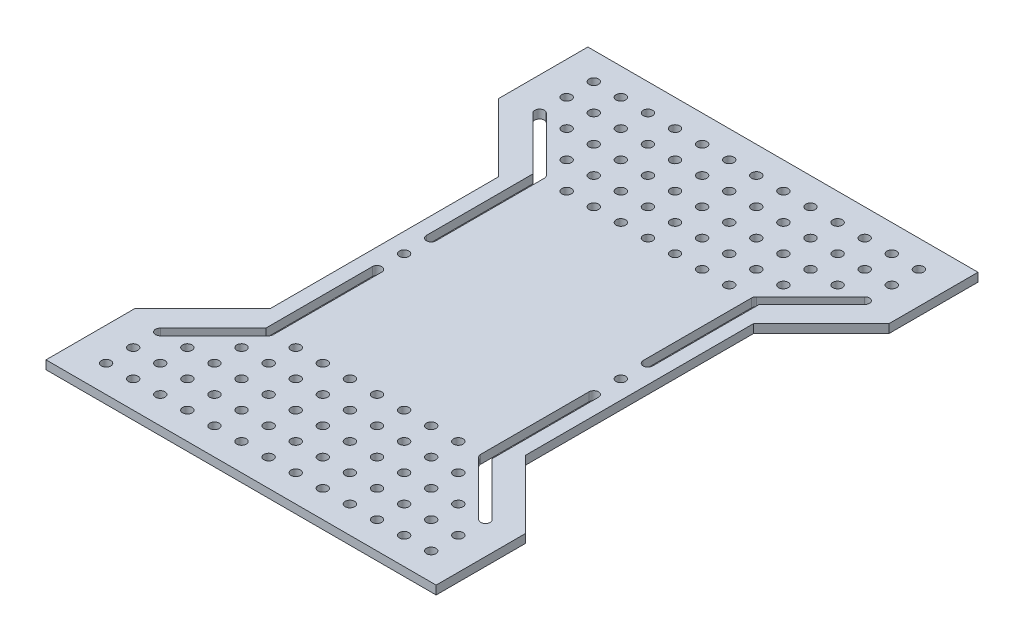
SolidWorks part; units mm, degrees
ref_plane "Alzado" through (0, 0, 0) normal (0, 0, 1) x (1, 0, 0)
ref_plane "Planta" through (0, 0, 0) normal (0, 1, 0) x (1, 0, 0)
ref_plane "Vista lateral" through (0, 0, 0) normal (1, 0, 0) x (0, 0, -1)
sketch "Croquis1" plane through (0, 0, 0) normal (0, 1, 0) x (1, 0, 0)
  point P0 (-19.4051, -35.8137)
  line B0 (25, 142.1) -> (25, 57.9)
  line B1 (25, 57.9) -> (0, 32.9)
  line B2 (0, 32.9) -> (0, 0)
  line B3 (0, 0) -> (144, 0)
  line B4 (144, 0) -> (144, 32.9)
  line B5 (144, 32.9) -> (119, 57.9)
  line B6 (119, 57.9) -> (119, 142.1)
  line B7 (119, 142.1) -> (144, 167.1)
  line B8 (144, 167.1) -> (144, 200)
  line B9 (144, 200) -> (0, 200)
  line B10 (0, 200) -> (0, 167.1)
  line B11 (0, 167.1) -> (25, 142.1)
  circle B12 centre (62.175, 20) radius 1.75
  circle B13 centre (92.175, 10) radius 1.75
  circle B14 centre (122.175, 10) radius 1.75
  circle B15 centre (132.175, 10) radius 1.75
  circle B16 centre (102.175, 10) radius 1.75
  circle B17 centre (112.175, 10) radius 1.75
  circle B18 centre (42.175, 20) radius 1.75
  circle B19 centre (52.175, 20) radius 1.75
  circle B20 centre (22.175, 20) radius 1.75
  circle B21 centre (32.175, 20) radius 1.75
  circle B22 centre (42.175, 10) radius 1.75
  circle B23 centre (52.175, 10) radius 1.75
  circle B24 centre (22.175, 10) radius 1.75
  circle B25 centre (32.175, 10) radius 1.75
  circle B26 centre (72.175, 10) radius 1.75
  circle B27 centre (122.175, 40) radius 1.75
  circle B28 centre (32.175, 50) radius 1.75
  circle B29 centre (102.175, 40) radius 1.75
  circle B30 centre (112.175, 40) radius 1.75
  circle B31 centre (72.175, 40) radius 1.75
  circle B32 centre (62.175, 40) radius 1.75
  circle B33 centre (92.175, 40) radius 1.75
  circle B34 centre (82.175, 40) radius 1.75
  circle B35 centre (122.175, 30) radius 1.75
  circle B36 centre (132.175, 30) radius 1.75
  circle B37 centre (102.175, 30) radius 1.75
  circle B38 centre (112.175, 30) radius 1.75
  circle B39 centre (42.175, 40) radius 1.75
  circle B40 centre (52.175, 40) radius 1.75
  circle B41 centre (22.175, 40) radius 1.75
  circle B42 centre (32.175, 40) radius 1.75
  circle B43 centre (132.175, 180) radius 1.75
  circle B44 centre (22.175, 190) radius 1.75
  circle B45 centre (12.175, 30) radius 1.75
  circle B46 centre (12.175, 170) radius 1.75
  circle B47 centre (12.175, 190) radius 1.75
  circle B48 centre (12.175, 180) radius 1.75
  circle B49 centre (12.175, 20) radius 1.75
  circle B50 centre (132.175, 190) radius 1.75
  circle B51 centre (92.175, 190) radius 1.75
  circle B52 centre (102.175, 190) radius 1.75
  circle B53 centre (112.175, 180) radius 1.75
  circle B54 centre (122.175, 180) radius 1.75
  circle B55 centre (92.175, 180) radius 1.75
  circle B56 centre (102.175, 180) radius 1.75
  circle B57 centre (32.175, 190) radius 1.75
  circle B58 centre (42.175, 190) radius 1.75
  circle B59 centre (42.175, 30) radius 1.75
  circle B60 centre (52.175, 30) radius 1.75
  circle B61 centre (22.175, 30) radius 1.75
  circle B62 centre (32.175, 30) radius 1.75
  circle B63 centre (82.175, 30) radius 1.75
  circle B64 centre (92.175, 30) radius 1.75
  circle B65 centre (62.175, 30) radius 1.75
  circle B66 centre (72.175, 30) radius 1.75
  circle B67 centre (92.175, 20) radius 1.75
  circle B68 centre (72.175, 20) radius 1.75
  circle B69 centre (122.175, 20) radius 1.75
  circle B70 centre (132.175, 20) radius 1.75
  circle B71 centre (102.175, 20) radius 1.75
  circle B72 centre (112.175, 20) radius 1.75
  circle B73 centre (32.175, 60) radius 1.75
  circle B74 centre (62.175, 50) radius 1.75
  circle B75 centre (72.175, 50) radius 1.75
  circle B76 centre (42.175, 50) radius 1.75
  circle B77 centre (52.175, 50) radius 1.75
  circle B78 centre (102.175, 50) radius 1.75
  circle B79 centre (112.175, 50) radius 1.75
  circle B80 centre (82.175, 50) radius 1.75
  circle B81 centre (92.175, 50) radius 1.75
  circle B82 centre (32.175, 70) radius 1.75
  circle B83 centre (112.175, 60) radius 1.75
  circle B84 centre (32.175, 80) radius 1.75
  circle B85 centre (112.175, 70) radius 1.75
  circle B86 centre (32.175, 90) radius 1.75
  circle B87 centre (112.175, 80) radius 1.75
  circle B88 centre (32.175, 100) radius 1.75
  circle B89 centre (112.175, 90) radius 1.75
  circle B90 centre (32.175, 110) radius 1.75
  circle B91 centre (112.175, 100) radius 1.75
  circle B92 centre (32.175, 120) radius 1.75
  circle B93 centre (112.175, 110) radius 1.75
  circle B94 centre (102.175, 160) radius 1.75
  circle B95 centre (112.175, 160) radius 1.75
  circle B96 centre (82.175, 160) radius 1.75
  circle B97 centre (92.175, 160) radius 1.75
  circle B98 centre (32.175, 170) radius 1.75
  circle B99 centre (42.175, 170) radius 1.75
  circle B100 centre (42.175, 150) radius 1.75
  circle B101 centre (52.175, 150) radius 1.75
  circle B102 centre (92.175, 150) radius 1.75
  circle B103 centre (82.175, 150) radius 1.75
  circle B104 centre (32.175, 150) radius 1.75
  circle B105 centre (112.175, 140) radius 1.75
  circle B106 centre (32.175, 130) radius 1.75
  circle B107 centre (112.175, 120) radius 1.75
  circle B108 centre (72.175, 190) radius 1.75
  circle B109 centre (82.175, 190) radius 1.75
  circle B110 centre (52.175, 190) radius 1.75
  circle B111 centre (62.175, 190) radius 1.75
  circle B112 centre (112.175, 190) radius 1.75
  circle B113 centre (122.175, 190) radius 1.75
  circle B114 centre (62.175, 150) radius 1.75
  circle B115 centre (72.175, 150) radius 1.75
  circle B116 centre (32.175, 140) radius 1.75
  circle B117 centre (42.175, 160) radius 1.75
  circle B118 centre (52.175, 160) radius 1.75
  circle B119 centre (32.175, 180) radius 1.75
  circle B120 centre (42.175, 180) radius 1.75
  circle B121 centre (82.175, 180) radius 1.75
  circle B122 centre (72.175, 180) radius 1.75
  circle B123 centre (22.175, 180) radius 1.75
  circle B124 centre (132.175, 170) radius 1.75
  circle B125 centre (32.175, 160) radius 1.75
  circle B126 centre (22.175, 160) radius 1.75
  circle B127 centre (22.175, 170) radius 1.75
  circle B128 centre (122.175, 160) radius 1.75
  circle B129 centre (102.175, 150) radius 1.75
  circle B130 centre (112.175, 150) radius 1.75
  circle B131 centre (62.175, 160) radius 1.75
  circle B132 centre (72.175, 160) radius 1.75
  circle B133 centre (92.175, 170) radius 1.75
  circle B134 centre (102.175, 170) radius 1.75
  circle B135 centre (112.175, 130) radius 1.75
  circle B136 centre (52.175, 180) radius 1.75
  circle B137 centre (62.175, 180) radius 1.75
  circle B138 centre (72.175, 170) radius 1.75
  circle B139 centre (82.175, 170) radius 1.75
  circle B140 centre (52.175, 170) radius 1.75
  circle B141 centre (62.175, 170) radius 1.75
  circle B142 centre (112.175, 170) radius 1.75
  circle B143 centre (122.175, 170) radius 1.75
  circle B144 centre (12.175, 10) radius 1.75
  circle B145 centre (62.175, 10) radius 1.75
  circle B146 centre (82.175, 20) radius 1.75
  circle B147 centre (82.175, 10) radius 1.75
sketch_block_instance "Bloque1-1"
sketch_block "Bloque1"
extrude "Saliente-Extruir1" add sketch "Croquis1" along normal blind 3.175
sketch "Croquis2" plane through (0, 3.175, 0) normal (0, 1, 0) x (1, 0, 0)
  line L0 (32.175, 150) -> (32.175, 110) construction
  line L3 (25, 100) -> (119, 100) construction
  line L4 (25, 142.1) -> (25, 57.9) construction
  line L5 (119, 57.9) -> (119, 142.1) construction
  line L9 (33.925, 150) -> (33.925, 110)
  line L10 (30.425, 150) -> (30.425, 110)
  line L11 (32.175, 50) -> (32.175, 90) construction
  line L12 (33.925, 50) -> (33.925, 90)
  line L13 (30.425, 50) -> (30.425, 90)
  line L14 (112.175, 50) -> (112.175, 90) construction
  line L20 (110.425, 50) -> (110.425, 90)
  line L23 (112.175, 150) -> (112.175, 110) construction
  line L24 (110.425, 150) -> (110.425, 110)
  line L25 (113.925, 150) -> (113.925, 110)
  line L26 (113.925, 50) -> (113.925, 90)
  arc A2 (33.925, 150) -> (30.425, 150) centre (32.175, 150) ccw
  arc A3 (30.425, 110) -> (33.925, 110) centre (32.175, 110) ccw
  circle A4 centre (32.175, 110) radius 1.75 construction
  arc A5 (33.925, 50) -> (30.425, 50) centre (32.175, 50) cw
  arc A6 (30.425, 90) -> (33.925, 90) centre (32.175, 90) cw
  circle A7 centre (32.175, 150) radius 1.75 construction
  arc A14 (110.425, 150) -> (113.925, 150) centre (112.175, 150) cw
  arc A15 (113.925, 110) -> (110.425, 110) centre (112.175, 110) cw
  circle A16 centre (112.175, 110) radius 1.75 construction
  circle A17 centre (112.175, 150) radius 1.75 construction
  arc A18 (110.425, 50) -> (113.925, 50) centre (112.175, 50) ccw
  arc A19 (113.925, 90) -> (110.425, 90) centre (112.175, 90) ccw
  point P4 (32.175, 130)
  point P15 (0, 0)
  point P22 (32.175, 70)
  point P25 (112.175, 70)
  point P38 (112.175, 130)
  point P43 (72, 71.6794)
extrude "Cortar-Extruir1" cut sketch "Croquis2" against normal through all
sketch "Croquis3" plane through (0, 3.175, 0) normal (0, 1, 0) x (1, 0, 0)
  line L0 (32.175, 150) -> (12.175, 170) construction
  line L1 (30.9376, 148.7626) -> (10.9376, 168.7626)
  line L2 (33.4124, 151.2374) -> (13.4124, 171.2374)
  line L3 (25, 100) -> (119, 100) construction
  line L5 (25, 100) -> (119, 100) construction
  line L6 (112.175, 50) -> (132.175, 30) construction
  line L7 (112.175, 150) -> (132.175, 170) construction
  line L8 (113.4124, 148.7626) -> (133.4124, 168.7626)
  line L9 (110.9376, 151.2374) -> (130.9376, 171.2374)
  line L10 (32.175, 50) -> (12.175, 30) construction
  line L11 (30.9376, 51.2374) -> (10.9376, 31.2374)
  line L12 (33.4124, 48.7626) -> (13.4124, 28.7626)
  line L13 (113.4124, 51.2374) -> (133.4124, 31.2374)
  line L16 (110.9376, 48.7626) -> (130.9376, 28.7626)
  arc A0 (30.9376, 148.7626) -> (33.4124, 151.2374) centre (32.175, 150) ccw
  arc A1 (13.4124, 171.2374) -> (10.9376, 168.7626) centre (12.175, 170) ccw
  circle A2 centre (12.175, 170) radius 1.75 construction
  arc A3 (33.925, 150) -> (30.425, 150) centre (32.175, 150) ccw construction
  arc A4 (113.4124, 148.7626) -> (110.9376, 151.2374) centre (112.175, 150) cw
  arc A5 (130.9376, 171.2374) -> (133.4124, 168.7626) centre (132.175, 170) cw
  arc A6 (30.9376, 51.2374) -> (33.4124, 48.7626) centre (32.175, 50) cw
  arc A7 (13.4124, 28.7626) -> (10.9376, 31.2374) centre (12.175, 30) cw
  circle A10 centre (132.175, 170) radius 1.75 construction
  arc A11 (113.925, 150) -> (110.425, 150) centre (112.175, 150) ccw construction
  arc A12 (113.4124, 51.2374) -> (110.9376, 48.7626) centre (112.175, 50) ccw
  arc A13 (130.9376, 28.7626) -> (133.4124, 31.2374) centre (132.175, 30) ccw
  point P2 (22.175, 160)
  point P8 (0, 0)
  point P20 (122.175, 160)
  point P27 (22.175, 40)
  point P37 (122.175, 40)
extrude "Cortar-Extruir2" cut sketch "Croquis3" against normal through all
